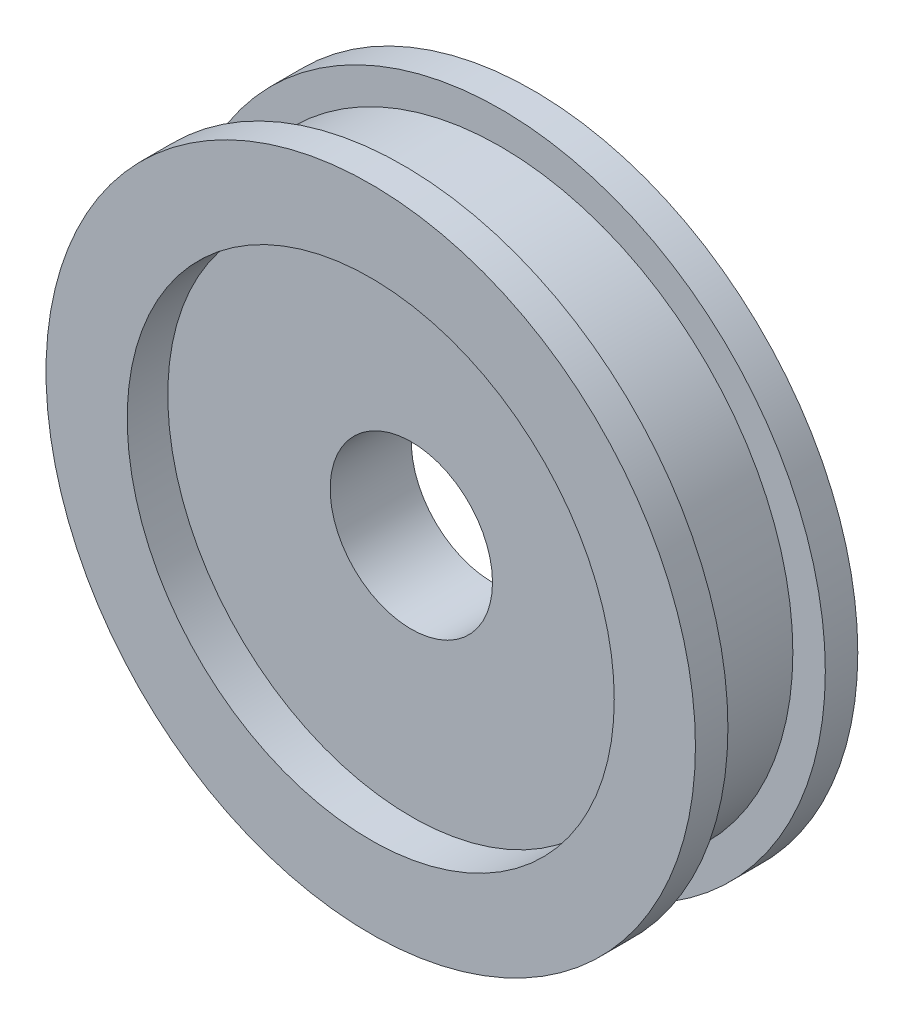
SolidWorks part; units mm, degrees
ref_plane "前视基准面" through (0, 0, 0) normal (0, 0, 1) x (1, 0, 0)
ref_plane "上视基准面" through (0, 0, 0) normal (0, 1, 0) x (1, 0, 0)
ref_plane "右视基准面" through (0, 0, 0) normal (1, 0, 0) x (0, 0, -1)
sketch "草图1" plane through (0, 0, 0) normal (0, 0, 1) x (1, 0, 0)
  circle A0 centre (0, 0) radius 20
  circle A1 centre (0, 0) radius 15
  circle A2 centre (0, 0) radius 5
extrude "凸台-拉伸2" add sketch "草图1" along normal mid plane 10 contours A0 A1 | A1 A2
sketch "草图2" plane through (0, 0, 5) normal (0, 0, 1) x (1, 0, 0)
  circle A0 centre (0, 0) radius 15
extrude "切除-拉伸1" cut sketch "草图2" against normal blind 5
sketch "草图3" plane through (0, 0, -5) normal (0, 0, -1) x (-1, 0, 0)
  circle A0 centre (0, 0) radius 15
extrude "切除-拉伸6" cut sketch "草图3" against normal through all
sketch "草图4" plane through (0, 0, 0) normal (0, 0, 1) x (1, 0, 0)
  circle A0 centre (0, 0) radius 15
extrude "凸台-拉伸3" add sketch "草图4" along normal mid plane 5
sketch "草图5" plane through (0, 0, 2.5) normal (0, 0, 1) x (1, 0, 0)
  circle A0 centre (0, 0) radius 5
extrude "切除-拉伸7" cut sketch "草图5" against normal through all
sketch "草图8" plane through (0, 0, 0) normal (0, 1, 0) x (1, 0, 0)
  line L0 (0, 0) -> (0, 9.4558) construction
  line L2 (-20, 5) -> (-20, -5) construction
  line L3 (-20, -3) -> (-18, -3)
  line L4 (-18, -3) -> (-18, 3)
  line L5 (-18, 3) -> (-20, 3)
  line L6 (-20, 3) -> (-20, -3)
revolve "切除-旋转1" cut sketch "草图8" angle 360 about L0
